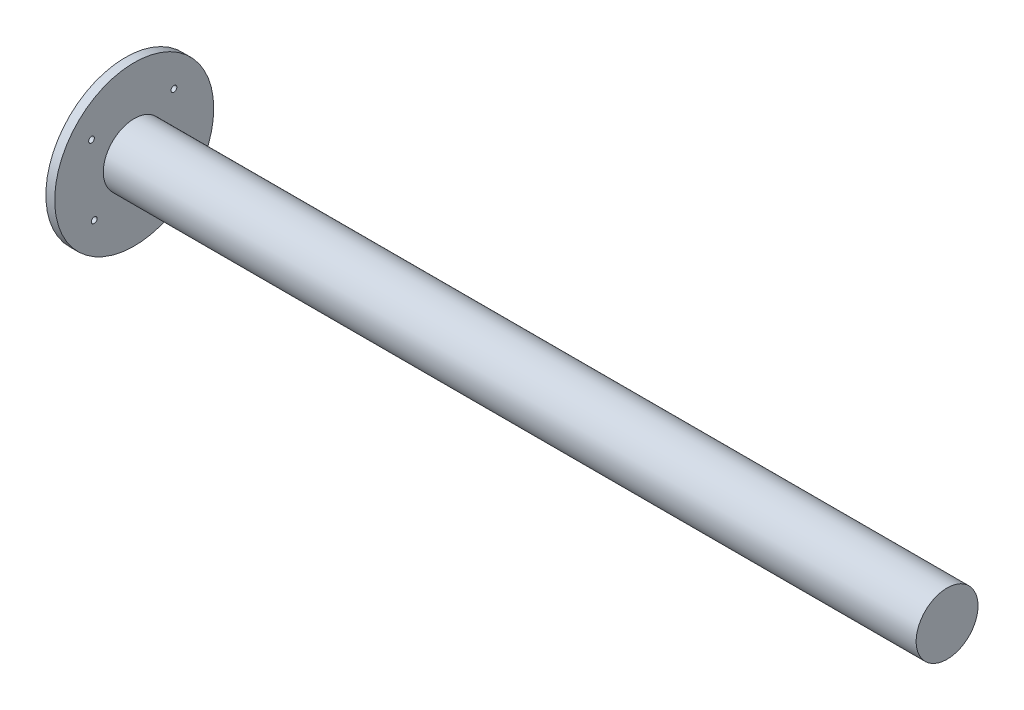
SolidWorks part; units mm, degrees
ref_plane "Alzado" through (0, 0, 0) normal (0, 0, 1) x (1, 0, 0)
ref_plane "Planta" through (0, 0, 0) normal (0, 1, 0) x (1, 0, 0)
ref_plane "Vista lateral" through (0, 0, 0) normal (1, 0, 0) x (0, 0, -1)
sketch "Croquis1" plane through (0, 0, 0) normal (1, 0, 0) x (0, 0, -1)
  circle A0 centre (0, 0) radius 45
  dimension "D1" = 90
extrude "Saliente-Extruir1" add sketch "Croquis1" along normal blind 5
sketch "Croquis2" plane through (5, 0, 0) normal (1, 0, 0) x (0, 0, -1)
  circle A1 centre (0, 0) radius 17.5
  point P0 (0, 0)
  point P1 (-23.3362, 20.1931)
  point P12 (23.3362, 20.1931)
  point P14 (23.3362, -20.1931)
  point P16 (-23.3362, -20.1931)
  dimension "D1" = 35
extrude "Saliente-Extruir2" add sketch "Croquis2" along normal blind 460
sketch "Croquis7" plane through (0, 0, 0) normal (-1, 0, 0) x (0, 0, 1)
  point P1 (24.1683, 19.2537)
  point P3 (-22.4862, 20.8424)
  point P4 (-23.7904, -19.4671)
  point P5 (22.6329, -20.9784)
hole_wizard "Taladro de margen para #45" positions "Croquis7" profile "Croquis8" hole size "#4" standard "Ansi Inch"
sketch "Croquis8" plane through (0, 19.2537, 24.1683) normal (0, 1, 0) x (0, 0, 1)
  line L0 (0, 0) -> (0, 5.9806)
  line L1 (0, 5.9806) -> (1.6319, 5)
  line L2 (1.6319, 5) -> (1.6319, 0)
  line L5 (1.6319, 0) -> (0, 0)
  line L10 (0, 5.9806) -> (-1.632, 5) construction
  line L11 (0, -6.35) -> (0, 107.95) construction
  dimension "Diámetro de taladro" = 3.2639
  dimension "Profundidad de taladro" = 5
  dimension "Ángulo de perforador" = 118
